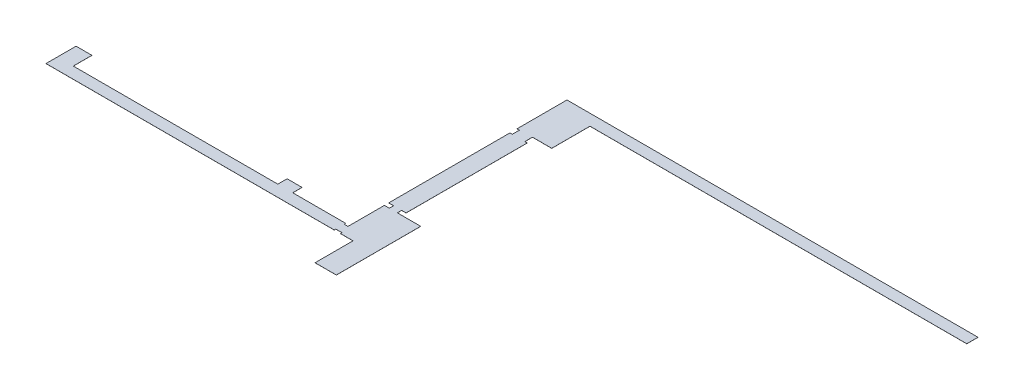
SolidWorks part; units mm, degrees
ref_plane "前视基准面" through (0, 0, 0) normal (0, 0, 1) x (1, 0, 0)
ref_plane "上视基准面" through (0, 0, 0) normal (0, 1, 0) x (1, 0, 0)
ref_plane "右视基准面" through (0, 0, 0) normal (1, 0, 0) x (0, 0, -1)
sketch "草图1" plane through (0, 0, 0) normal (0, 1, 0) x (1, 0, 0)
  line L0 (0, 0) -> (-10316.6951, 0)
  line L1 (-10316.6951, 0) -> (-10316.6951, -8070)
  line L2 (-10316.6951, -8070) -> (-9931.6951, -8070)
  line L3 (-9931.6951, -8070) -> (-9931.6951, -9210)
  line L4 (-9931.6951, -9210) -> (-10316.6951, -9210)
  line L5 (-10316.6951, -9210) -> (-10316.6951, -28750)
  line L6 (-10316.6951, -28750) -> (-9516.6951, -28750)
  line L7 (-9516.6951, -28750) -> (-9516.6951, -29440)
  line L8 (-9516.6951, -29440) -> (-10316.6951, -29440)
  line L9 (-10316.6951, -29440) -> (-10316.6951, -35320)
  line L10 (-10316.6951, -35320) -> (-10916.6951, -35320)
  line L11 (-10916.6951, -35320) -> (-10916.6951, -35070)
  line L12 (-10916.6951, -35070) -> (-54856.6951, -35070)
  line L13 (-54856.6951, -35070) -> (-54856.6951, -32070)
  line L14 (-54856.6951, -32070) -> (-57406.6951, -32070)
  line L15 (-57406.6951, -32070) -> (-57406.6951, -36920)
  line L16 (-57406.6951, -36920) -> (-10916.6951, -36920)
  line L17 (-10916.6951, -36920) -> (-10916.6951, -36670)
  line L18 (-10916.6951, -36670) -> (-9896.6951, -36670)
  line L19 (-9896.6951, -36670) -> (-9896.6951, -36920)
  line L20 (-9896.6951, -36920) -> (-7896.6951, -36920)
  line L21 (-7896.6951, -36920) -> (-7896.6951, -43040)
  line L22 (-7896.6951, -43040) -> (-4466.6951, -43040)
  line L23 (-4466.6951, -43040) -> (-4466.6951, -29440)
  line L24 (-4466.6951, -29440) -> (-8236.6951, -29440)
  line L25 (-8236.6951, -29440) -> (-8236.6951, -28750)
  line L26 (-8236.6951, -28750) -> (-7516.6951, -28750)
  line L27 (-7516.6951, -28750) -> (-7516.6951, -9210)
  line L28 (-7516.6951, -9210) -> (-7901.6951, -9210)
  line L29 (-7901.6951, -9210) -> (-7901.6951, -8070)
  line L30 (-7901.6951, -7980) -> (-4796.6951, -7980)
  line L31 (-4796.6951, -7980) -> (-4796.6951, -1810)
  line L32 (-4796.6951, -1810) -> (55963.3049, -1810)
  line L33 (55963.3049, -1810) -> (55963.3049, 0)
  line L34 (55963.3049, 0) -> (0, 0)
  line L35 (-7901.6951, -8070) -> (-7901.6951, -7980)
  line L36 (-19466.6951, -35070) -> (-19466.6951, -33570)
  line L37 (-19466.6951, -33570) -> (-21876.6951, -33570)
  line L38 (-21876.6951, -33570) -> (-21876.6951, -35070)
  dimension "D1" = 8070
  dimension "D2" = 60760
  dimension "D3" = 1810
  dimension "D4" = 90
  dimension "D5" = 1140
  dimension "D6" = 1140
  dimension "D7" = 2030
  dimension "D8" = 2800
  dimension "D9" = 385
  dimension "D10" = 800
  dimension "D11" = 1280
  dimension "D12" = 3770
  dimension "D13" = 690
  dimension "D14" = 19540
  dimension "D15" = 13600
  dimension "D16" = 5850
  dimension "D17" = 2000
  dimension "D18" = 600
  dimension "D19" = 1020
  dimension "D20" = 1850
  dimension "D21" = 250
  dimension "D22" = 250
  dimension "D23" = 250
  dimension "D24" = 7480
  dimension "D25" = 43940
  dimension "D26" = 2550
  dimension "D27" = 3000
  dimension "D28" = 8550
  dimension "D29" = 10960
  dimension "D30" = 1500
  dimension "D31" = 5520
extrude "凸台-拉伸1" add sketch "草图1" along normal blind 10 contours L37 L38 L12 L36 | L29 L35 L30 L31 L32 L33 L34 L0 L1 L2 L3 L4 L5 L6 L7 L8 L9 L10 L11 L12 L13 L14 L15 L16 L17 L18 L19 L20 L21 L22 L23 L24 L25 L26 L27 L28
